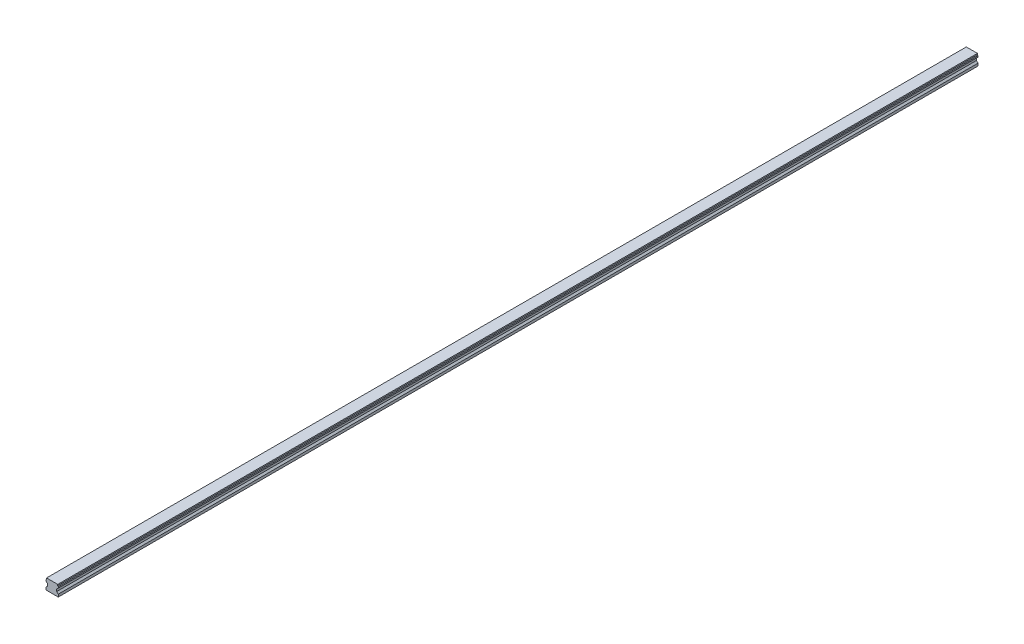
SolidWorks part; units mm, degrees
material "Plain Carbon Steel"
ref_plane "Frontal Plane" through (0, 0, 0) normal (0, 0, 1) x (1, 0, 0)
ref_plane "Horizontal Plane" through (0, 0, 0) normal (0, 1, 0) x (1, 0, 0)
ref_plane "Profile Plane" through (0, 0, 0) normal (1, 0, 0) x (0, 0, -1)
sketch "Sketch1" plane through (0, 0, 0) normal (0, 0, 1) x (1, 0, 0)
  line L1 (9.1, 0) -> (9.1, -2)
  line L2 (9.1, -2) -> (10, -2.9)
  line L3 (10, -2.9) -> (10, -4.9)
  line L4 (10, -4.9) -> (7.5, -7.4)
  line L5 (7.5, -7.4) -> (7.5, -10.9)
  line L6 (7.5, -10.9) -> (10, -13.4)
  line L10 (0, 0) -> (0, -22775.0845) construction
  line L15 (9.1, 0) -> (-9.1, 0)
  line L16 (10, -13.4) -> (10, -17.5)
  line L17 (10, -17.5) -> (-10, -17.5)
  line L18 (-10, -13.4) -> (-10, -17.5)
  line L19 (-7.5, -10.9) -> (-10, -13.4)
  line L20 (-7.5, -7.4) -> (-7.5, -10.9)
  line L21 (-10, -4.9) -> (-7.5, -7.4)
  line L22 (-10, -2.9) -> (-10, -4.9)
  line L23 (-9.1, -2) -> (-10, -2.9)
  line L24 (-9.1, 0) -> (-9.1, -2)
  point P15 (0, -17.5)
  point P17 (0, 0)
  point P20 (0, 0)
  dimension "D1" = 10
  dimension "D2" = 9.1
  dimension "D3" = 2.5
  dimension "D4" = 17.5
  dimension "D5" = 2
  dimension "D6" = 2
  dimension "D7" = 3.5
  dimension "D8" = 135
extrude "Boss-Extrude1" add sketch "Sketch1" against normal blind 1500
